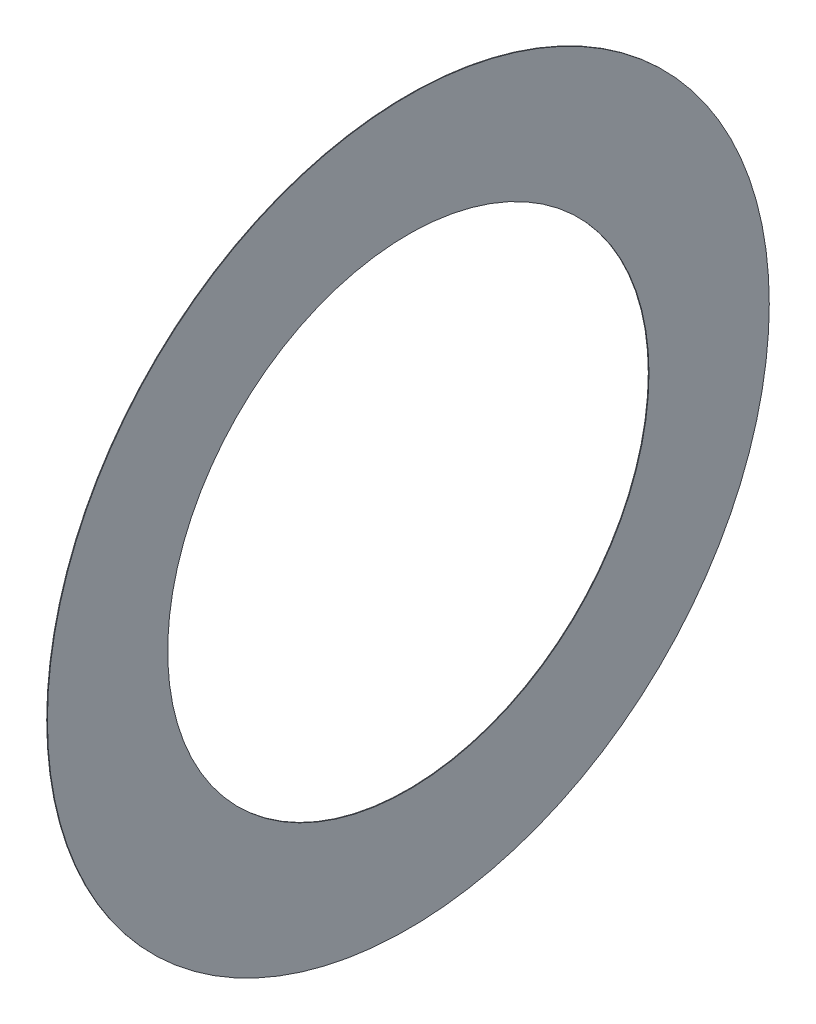
SolidWorks part; units mm, degrees
ref_plane "Front Plane" through (0, 0, 0) normal (0, 0, 1) x (1, 0, 0)
ref_plane "Top Plane" through (0, 0, 0) normal (0, 1, 0) x (1, 0, 0)
ref_plane "Right Plane" through (0, 0, 0) normal (1, 0, 0) x (0, 0, -1)
sketch "Sketch1" plane through (0, 0, 0) normal (1, 0, 0) x (0, 0, -1)
  circle A2 centre (0, 0) radius 9.525
  circle A3 centre (0, 0) radius 14.2875
  dimension "D3" = 28.575
  dimension "D4" = 19.05
extrude "Boss-Extrude1" add sketch "Sketch1" along normal blind 0.0254
